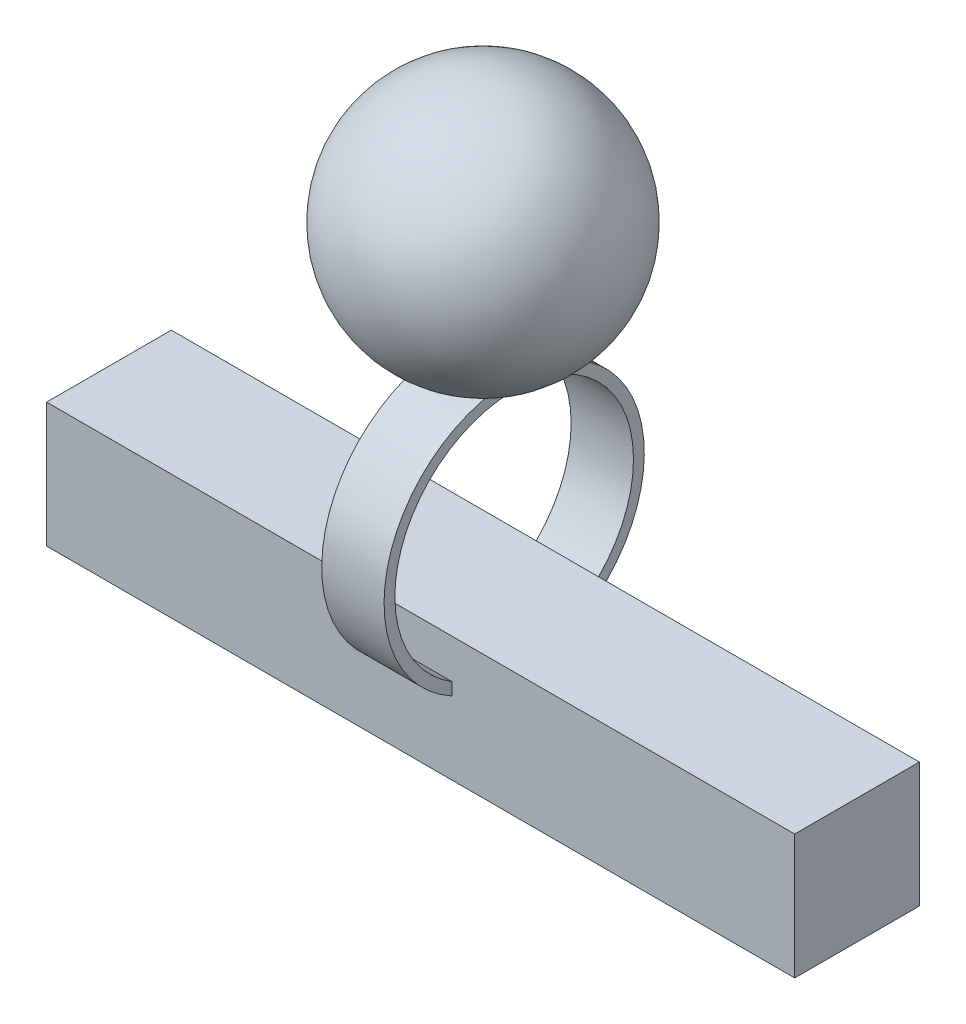
SolidWorks part; units mm, degrees
material "PLA"
ref_plane "Front Plane" through (0, 0, 0) normal (0, 0, 1) x (1, 0, 0)
ref_plane "Top Plane" through (0, 0, 0) normal (0, 1, 0) x (1, 0, 0)
ref_plane "Right Plane" through (0, 0, 0) normal (1, 0, 0) x (0, 0, -1)
sketch "Sketch1" plane through (0, 0, 0) normal (1, 0, 0) x (0, 0, -1)
  line L1 (-2.5, 2.5) -> (2.5, 2.5)
  line L2 (-2.5, 2.5) -> (-2.5, -2.5)
  line L3 (-2.5, -2.5) -> (2.5, -2.5)
  line L4 (2.5, 2.5) -> (2.5, -2.5)
  line L5 (-2.5, 2.5) -> (2.5, -2.5) construction
  line L6 (-2.5, -2.5) -> (2.5, 2.5) construction
  point P0 (0, 0)
  dimension "D1" = 5
  dimension "D2" = 5
extrude "Boss-Extrude1" add sketch "Sketch1" along normal mid plane 30
sketch "Sketch3" plane through (0, 0, 0) normal (1, 0, 0) x (0, 0, -1)
  line L0 (0, 10) -> (0, 20) construction
  line L1 (0, 10) -> (0, 20)
  arc A0 (0, 20) -> (0, 10) centre (0, 15) ccw
  point P5 (0, 7.3283)
  point P6 (0, 0)
  point P7 (0, 0)
  point P8 (0, 17.9152)
  point P9 (0, 17.3183)
  dimension "D1" = 10
  dimension "D2" = 15
revolve "Revolve1" add sketch "Sketch3" angle 360 about L0
sketch "Sketch4" plane through (0, 0, 0) normal (1, 0, 0) x (0, 0, -1)
  line L0 (0, -1.4439) -> (0, 11.7551) construction
  line L2 (-2.5, 2.5) -> (2.5, 2.5) construction
  line L3 (-2.5, 2.5) -> (-2.5, -2.5) construction
  line L4 (-2.5, -2.5) -> (2.5, -2.5) construction
  line L5 (2.5, 2.5) -> (2.5, -2.5) construction
  line L6 (-2.5, 2.5) -> (2.5, -2.5) construction
  line L7 (-2.5, -2.5) -> (2.5, 2.5) construction
  circle A2 centre (0, 5) radius 5
  point P5 (0, 0)
  dimension "D1" = 10
sketch "Sketch5" plane through (0, 0, 2.5) normal (0, 0, 1) x (1, 0, 0)
  line L1 (-1.25, 0.9199) -> (1.25, 0.9199)
  line L2 (-1.25, 0.9199) -> (-1.25, 0.4199)
  line L3 (-1.25, 0.4199) -> (1.25, 0.4199)
  line L4 (1.25, 0.9199) -> (1.25, 0.4199)
  line L5 (-1.25, 0.9199) -> (1.25, 0.4199) construction
  line L6 (-1.25, 0.4199) -> (1.25, 0.9199) construction
  point P0 (0, 0.6699)
  point P6 (0, 0)
  point P7 (0, 0)
  point P8 (0, 0)
  point P9 (0, 0)
  dimension "D1" = 2.5
  dimension "D2" = 0.5
sweep "Sweep1" add profiles "Sketch5" path "Sketch4"
